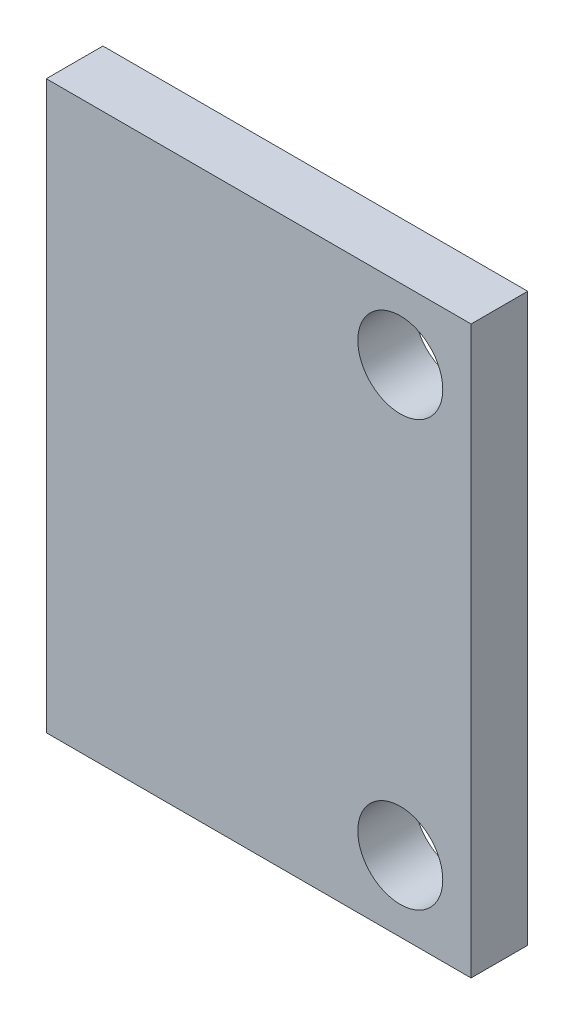
SolidWorks part; units mm, degrees
ref_plane "正面" through (0, 0, 0) normal (0, 0, 1) x (1, 0, 0)
ref_plane "平面" through (0, 0, 0) normal (0, 1, 0) x (1, 0, 0)
ref_plane "右側面" through (0, 0, 0) normal (1, 0, 0) x (0, 0, -1)
sketch "ｽｹｯﾁ1" plane through (0, 0, 0) normal (0, 0, 1) x (1, 0, 0)
  line L1 (7.5, -10) -> (-7.5, -10)
  line L2 (7.5, -10) -> (7.5, 10)
  line L3 (7.5, 10) -> (-7.5, 10)
  line L4 (-7.5, -10) -> (-7.5, 10)
  line L5 (7.5, -10) -> (-7.5, 10) construction
  line L6 (7.5, 10) -> (-7.5, -10) construction
  point P0 (0, 0)
  dimension "D1" = 15
  dimension "D2" = 20
extrude "ﾎﾞｽ - 押し出し1" add sketch "ｽｹｯﾁ1" along normal blind 2
sketch "ｽｹｯﾁ2" plane through (0, 0, 2) normal (0, 0, 1) x (1, 0, 0)
  line L0 (7.5, -10) -> (7.5, 10) construction
  line L1 (-7.5, -10) -> (7.5, -10) construction
  line L2 (7.5, 10) -> (-7.5, 10) construction
  circle A0 centre (5, 7.5) radius 1.5
  circle A1 centre (5, -7.5) radius 1.5
  point P6 (0, 0)
  dimension "D1" = 3
  dimension "D2" = 2.5
  dimension "D3" = 2.5
  dimension "D4" = 2.5
extrude "ｶｯﾄ - 押し出し1" cut sketch "ｽｹｯﾁ2" against normal blind 2
